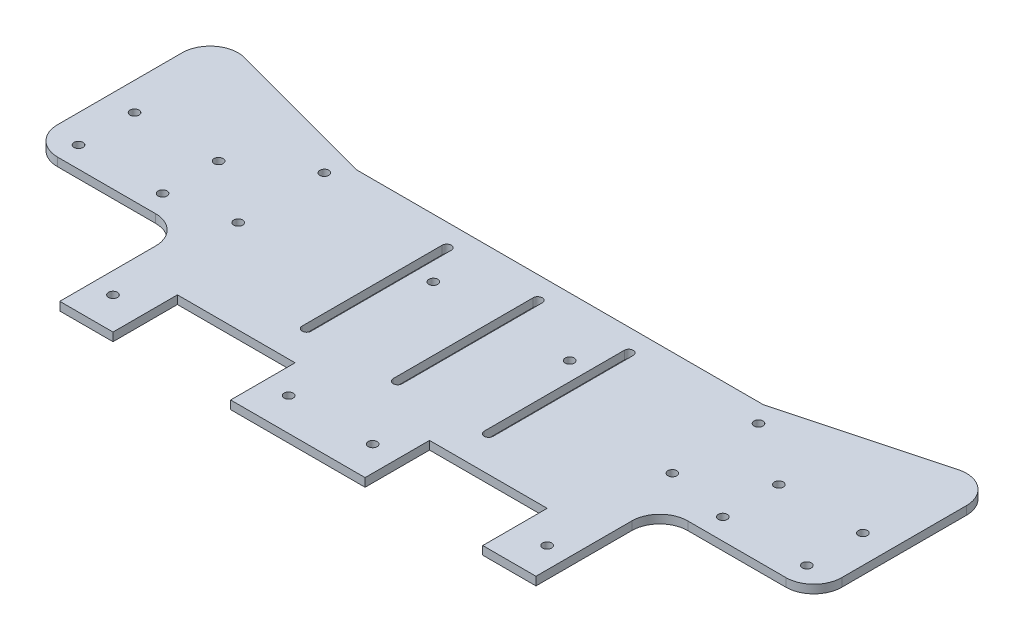
SolidWorks part; units mm, degrees
ref_plane "Front Plane" through (0, 0, 0) normal (0, 0, 1) x (1, 0, 0)
ref_plane "Top Plane" through (0, 0, 0) normal (0, 1, 0) x (1, 0, 0)
ref_plane "Right Plane" through (0, 0, 0) normal (1, 0, 0) x (0, 0, -1)
sketch "Sketch1" plane through (0, 0, 0) normal (0, 1, 0) x (1, 0, 0)
  line L4 (0, 0) -> (170, 0)
  line L5 (0, 0) -> (0, 330) construction
  line L6 (0, 330) -> (170, 330) construction
  line L7 (170, 0) -> (170, 330) construction
  line L8 (85, 330) -> (225, 367.5129)
  line L9 (-55, 367.5129) -> (85, 330)
  line L10 (-55, 367.5129) -> (-55, 300)
  line L11 (-55, 300) -> (0, 300)
  line L12 (225, 300) -> (225, 367.5129)
  line L13 (225, 300) -> (170, 300)
  line L14 (0, 300) -> (0, 0)
  line L15 (170, 300) -> (170, 0)
  dimension "D1" = 30
  dimension "D2" = 330
  dimension "D3" = 15
  dimension "D4" = 15
  dimension "D5" = 55
  dimension "D6" = 170
extrude "Boss-Extrude1" add sketch "Sketch1" along normal blind 3
fillet "Fillet1" radius 200 1 edges at (85, 1.5, -330)
fillet "Fillet2" radius 10 8 edges at (0, 1.5, 0) (170, 1.5, 0) (170, 1.5, -300) (0, 1.5, -300) (-55, 1.5, -300) (225, 1.5, -300) (225, 1.5, -367.5129) (-55, 1.5, -367.5129)
sketch "Sketch2" plane through (0, 3, 0) normal (0, 1, 0) x (1, 0, 0)
  line L0 (85, 337.0552) -> (85, 0)
  line L1 (10, 0) -> (160, 0) construction
  line L2 (0, 32.5) -> (170, 32.5) construction
  line L3 (0, 290) -> (0, 10) construction
  line L4 (170, 10) -> (170, 290) construction
  circle A0 centre (85, 80) radius 47.5
  arc A1 (33.2362, 343.8701) -> (136.7638, 343.8701) centre (85, 537.0552) ccw construction
  dimension "D1" = 95
  dimension "D2" = 32.5
extrude "Cut-Extrude2" cut sketch "Sketch2" against normal through all contours L0 A0 | L0 A0
sketch "Sketch3" plane through (0, 3, 0) normal (0, 1, 0) x (1, 0, 0)
  line L1 (19, 278.8) -> (61, 278.8)
  line L2 (19, 278.8) -> (19, 255.8)
  line L3 (19, 255.8) -> (61, 255.8)
  line L4 (61, 278.8) -> (61, 255.8)
  line L5 (109, 278.8) -> (151, 278.8)
  line L6 (109, 278.8) -> (109, 255.8)
  line L7 (109, 255.8) -> (151, 255.8)
  line L8 (151, 278.8) -> (151, 255.8)
  line L9 (19, 19) -> (61, 19)
  line L10 (19, 19) -> (19, 0)
  line L11 (19, 0) -> (61, 0)
  line L12 (61, 19) -> (61, 0)
  line L13 (109, 19) -> (151, 19)
  line L14 (109, 19) -> (109, 0)
  line L15 (109, 0) -> (151, 0)
  line L16 (151, 19) -> (151, 0)
  line L17 (-45, 300) -> (-10, 300) construction
  line L18 (0, 290) -> (0, 10) construction
  line L19 (170, 10) -> (170, 290) construction
  line L20 (280, 0) -> (-110, 0) construction
  dimension "D1" = 21.2
  dimension "D2" = 23
  dimension "D3" = 19
  dimension "D4" = 42
  dimension "D5" = 19
  dimension "D6" = 19
extrude "Cut-Extrude3" cut sketch "Sketch3" against normal through all
sketch "Sketch4" plane through (0, 3, 0) normal (0, 1, 0) x (1, 0, 0)
  circle A0 centre (85, 80) radius 58 construction
  circle A1 centre (85, 80) radius 53 construction
  circle A2 centre (85, 133) radius 1.6
  circle A3 centre (122.4767, 117.4767) radius 1.6
  circle A4 centre (138, 80) radius 1.6
  circle A5 centre (122.4767, 42.5233) radius 1.6
  circle A6 centre (85, 27) radius 1.6
  circle A7 centre (47.5233, 42.5233) radius 1.6
  circle A8 centre (32, 80) radius 1.6
  circle A9 centre (47.5233, 117.4767) radius 1.6
  point P22 (85, 80)
  dimension "D1" = 116
  dimension "D2" = 5
  dimension "D3" = 3.2
  dimension "D4" = 8
extrude "Cut-Extrude5" cut sketch "Sketch4" against normal through all
sketch "Sketch5" plane through (0, 3, 0) normal (0, 1, 0) x (1, 0, 0)
  circle A0 centre (7.5, 312) radius 1.6
  circle A1 centre (7.5, 267.3) radius 1.6
  circle A2 centre (7.5, 222.3) radius 1.6
  circle A3 centre (7.5, 97.5) radius 1.6
  circle A4 centre (7.5, 7.5) radius 1.6
  circle A5 centre (7.5, 52.5) radius 1.6
  circle A6 centre (70, 7.5) radius 1.6
  circle A7 centre (100, 7.5) radius 1.6
  circle A8 centre (162.5, 7.5) radius 1.6
  circle A9 centre (162.5, 52.5) radius 1.6
  circle A10 centre (162.5, 97.5) radius 1.6
  circle A11 centre (162.5, 222.3) radius 1.6
  circle A12 centre (162.5, 267.3) radius 1.6
  circle A13 centre (162.5, 312) radius 1.6
  circle A14 centre (162.5, 342.755) radius 1.6
  circle A15 centre (109.3378, 328.5102) radius 1.6
  circle A16 centre (60.6622, 328.5102) radius 1.6
  circle A17 centre (7.5, 342.755) radius 1.6
  circle A18 centre (70, 267.5) radius 1.6
  circle A19 centre (100, 267.5) radius 1.6
  dimension "D1" = 3.2
extrude "Cut-Extrude6" cut sketch "Sketch5" against normal through all
sketch "Sketch6" plane through (0, 0, 0) normal (0, -1, 0) x (1, 0, 0)
  line L6 (0, -290) -> (0, -10) construction
  line L7 (0, -45) -> (-66, -45)
  line L8 (0, -45) -> (0, -60)
  line L9 (0, -60) -> (-66, -60)
  line L10 (-66, -45) -> (-66, -60)
  line L11 (0, -45) -> (-66, -45) construction
  line L12 (170, -10) -> (170, -290) construction
  line L13 (170, -60) -> (236, -60)
  line L14 (170, -60) -> (170, -45)
  line L15 (170, -45) -> (236, -45)
  line L16 (236, -60) -> (236, -45)
  line L17 (170, -60) -> (236, -60) construction
  circle A0 centre (191, -52.5) radius 1.6
  circle A1 centre (215, -52.5) radius 1.6
  circle A2 centre (-45, -52.5) radius 1.6
  circle A3 centre (-21, -52.5) radius 1.6
  dimension "D3" = 66
  dimension "D5" = 3.2
  dimension "D1" = 66
  dimension "D2" = 15
  dimension "D4" = 15
extrude "Boss-Extrude2" add sketch "Sketch6" against normal blind 3
fillet "Fillet3" radius 5 14 edges at (236, 1.5, -60) (236, 1.5, -45) (-66, 1.5, -45) (-66, 1.5, -60) (0, 1.5, -60) (0, 1.5, -45) (151, 1.5, 0) (151, 1.5, -19) (109, 1.5, -19) (109, 1.5, 0) (61, 1.5, 0) (19, 1.5, 0) (170, 1.5, -60) (170, 1.5, -45)
sketch "Sketch7" plane through (0, 3, 0) normal (0, 1, 0) x (1, 0, 0)
  circle A0 centre (130, 171.5) radius 1.6
  circle A1 centre (145, 171.5) radius 1.6
  circle A2 centre (145, 159.5) radius 1.6
  circle A3 centre (130, 159.5) radius 1.6
  circle A4 centre (25, 171.5) radius 1.6
  circle A5 centre (40, 171.5) radius 1.6
  circle A6 centre (40, 159.5) radius 1.6
  circle A7 centre (25, 159.5) radius 1.6
  circle A8 centre (70, 242) radius 1.6
  circle A9 centre (100, 242) radius 1.6
  dimension "D1" = 3.2
extrude "Cut-Extrude7" cut sketch "Sketch7" against normal through all
sketch "Sketch8" plane through (0, 3, 0) normal (0, 1, 0) x (1, 0, 0)
  line L0 (-45, 364.4806) -> (215, 364.4806)
  line L1 (215, 364.4806) -> (136.7638, 343.8701)
  line L2 (136.7638, 343.8701) -> (33.2362, 343.8701) construction
  line L3 (33.2362, 343.8701) -> (-45, 364.4806)
  arc A0 (-42.4118, 364.1399) -> (-55, 354.4806) centre (-45, 354.4806) ccw construction
  arc A1 (225, 354.4806) -> (212.4118, 364.1399) centre (215, 354.4806) ccw construction
  arc A2 (33.2362, 343.8701) -> (136.7638, 343.8701) centre (85, 537.0552) ccw
  arc A3 (33.2362, 343.8701) -> (136.7638, 343.8701) centre (85, 537.0552) ccw construction
extrude "Boss-Extrude4" [suppressed] add sketch "Sketch8" against normal blind 3
sketch "Sketch9" plane through (0, 3, 0) normal (0, 1, 0) x (1, 0, 0)
  line L0 (-55, 354.4806) -> (-55, 310) construction
  line L1 (-45, 300) -> (-10, 300) construction
  line L2 (-55, 335) -> (-5, 335) construction
  line L3 (-5, 335) -> (-5, 300) construction
  line L4 (-45, 307.5) -> (-45, 327.5) construction
  line L5 (-45, 327.5) -> (-15, 327.5) construction
  line L6 (-15, 327.5) -> (-15, 307.5) construction
  line L7 (-15, 307.5) -> (-45, 307.5) construction
  line L8 (85, 337.0552) -> (85, 300) construction
  circle A0 centre (-45, 307.5) radius 1.6
  circle A1 centre (-15, 307.5) radius 1.6
  circle A2 centre (-45, 327.5) radius 1.6
  circle A3 centre (-15, 327.5) radius 1.6
  arc A4 (33.2362, 343.8701) -> (136.7638, 343.8701) centre (85, 537.0552) ccw construction
  circle A5 centre (185, 307.5) radius 1.6
  circle A6 centre (185, 327.5) radius 1.6
  circle A7 centre (215, 307.5) radius 1.6
  circle A8 centre (215, 327.5) radius 1.6
  dimension "D1" = 10
  dimension "D2" = 7.5
  dimension "D7" = 3.2
  dimension "D3" = 35
  dimension "D4" = 50
  dimension "D5" = 7.5
  dimension "D6" = 10
extrude "Cut-Extrude8" cut sketch "Sketch9" against normal through all
sketch "Sketch10" plane through (0, 3, 0) normal (0, 1, 0) x (1, 0, 0)
  line L0 (66, 0) -> (104, 0) construction
  line L1 (-66, 255.8) -> (236, 255.8)
  line L2 (-66, 255.8) -> (-66, 0)
  line L3 (-66, 0) -> (236, 0)
  line L4 (236, 255.8) -> (236, 0)
  line L5 (-66, 50) -> (-66, 55) construction
  line L6 (236, 55) -> (236, 50) construction
  line L7 (19, 255.8) -> (61, 255.8) construction
extrude "Cut-Extrude9" cut sketch "Sketch10" against normal blind 10
sketch "Sketch11" plane through (0, 3, 0) normal (0, 1, 0) x (1, 0, 0)
  line L1 (33.2362, 343.8701) -> (12.5, 349.4263)
  line L2 (33.2362, 343.8701) -> (-42.4118, 364.1399) construction
  line L3 (12.5, 349.4263) -> (157.5, 349.4263)
  line L4 (212.4118, 364.1399) -> (136.7638, 343.8701) construction
  line L5 (136.7638, 343.8701) -> (157.5, 349.4263)
  arc A0 (33.2362, 343.8701) -> (136.7638, 343.8701) centre (85, 537.0552) ccw
  arc A1 (33.2362, 343.8701) -> (136.7638, 343.8701) centre (85, 537.0552) ccw construction
  point P8 (0, 0)
  dimension "D1" = 145
extrude "Boss-Extrude5" add sketch "Sketch11" against normal up to surface (3 mm away) up to face at (185, 0, -309.1)
sketch "Sketch12" plane through (0, 3, 0) normal (0, 1, 0) x (1, 0, 0)
  line L0 (52.5, 341.4263) -> (117.5, 341.4263) construction
  line L2 (157.5, 349.4263) -> (12.5, 349.4263) construction
  line L3 (50.9, 341.4263) -> (54.1, 341.4263) construction
  line L4 (50.9, 341.4263) -> (50.9, 291.4263)
  line L5 (50.9, 291.4263) -> (54.1, 291.4263) construction
  line L6 (54.1, 341.4263) -> (54.1, 291.4263)
  line L7 (83.4, 341.4263) -> (86.6, 341.4263) construction
  line L8 (83.4, 341.4263) -> (83.4, 291.4263)
  line L9 (83.4, 291.4263) -> (86.6, 291.4263) construction
  line L10 (86.6, 341.4263) -> (86.6, 291.4263)
  line L15 (115.9, 341.4263) -> (119.1, 341.4263) construction
  line L16 (115.9, 341.4263) -> (115.9, 291.4263)
  line L17 (115.9, 291.4263) -> (119.1, 291.4263) construction
  line L18 (119.1, 341.4263) -> (119.1, 291.4263)
  arc A0 (86.6, 341.4263) -> (83.4, 341.4263) centre (85, 341.4263) ccw
  arc A1 (119.1, 341.4263) -> (115.9, 341.4263) centre (117.5, 341.4263) ccw
  arc A2 (54.1, 341.4263) -> (50.9, 341.4263) centre (52.5, 341.4263) ccw
  arc A3 (50.9, 291.4263) -> (54.1, 291.4263) centre (52.5, 291.4263) ccw
  arc A4 (83.4, 291.4263) -> (86.6, 291.4263) centre (85, 291.4263) ccw
  arc A5 (115.9, 291.4263) -> (119.1, 291.4263) centre (117.5, 291.4263) ccw
  point P5 (0, 0)
  point P22 (85, 349.4263)
  dimension "D1" = 65
  dimension "D2" = 3.2
  dimension "D3" = 8
  dimension "D4" = 50
extrude "Cut-Extrude10" cut sketch "Sketch12" against normal blind 10
